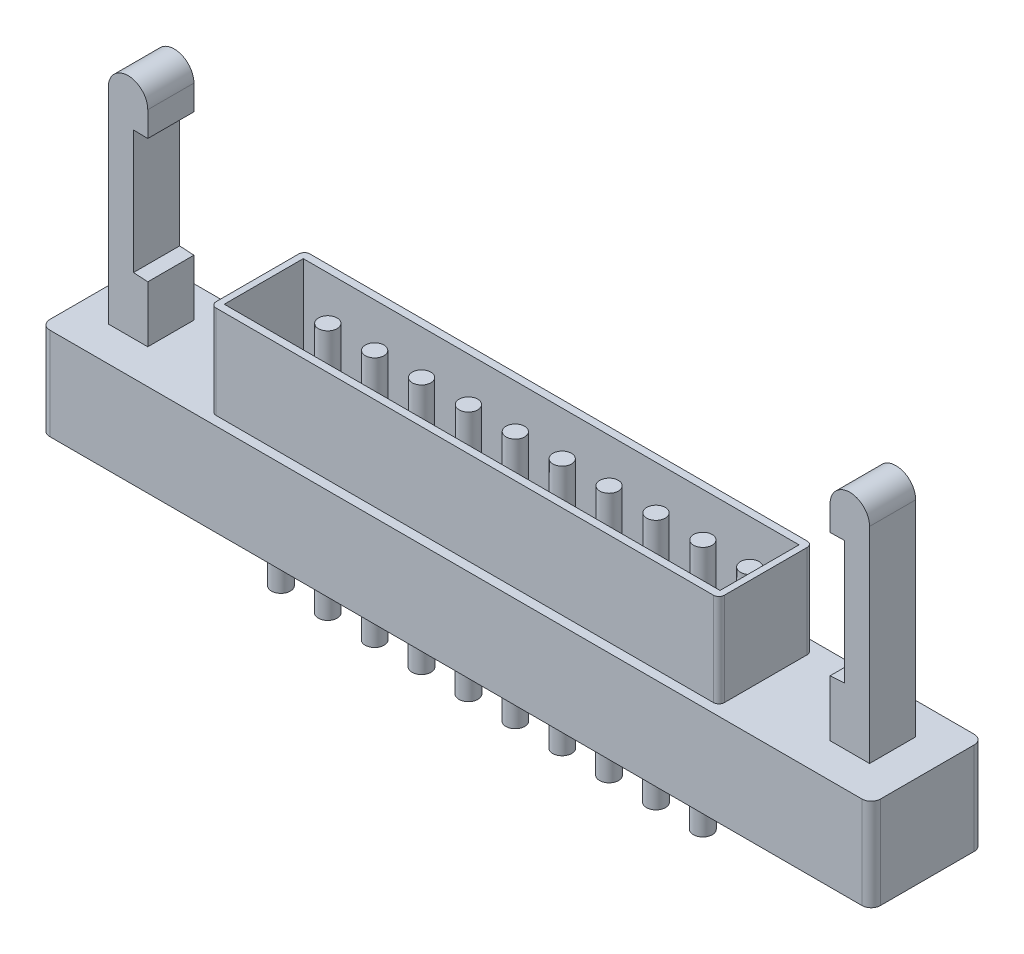
SolidWorks part; units mm, degrees
ref_plane "Спереди" through (0, 0, 0) normal (0, 0, 1) x (1, 0, 0)
ref_plane "Сверху" through (0, 0, 0) normal (0, 1, 0) x (1, 0, 0)
ref_plane "Справа" through (0, 0, 0) normal (1, 0, 0) x (0, 0, -1)
sketch "Эскиз2" plane through (0, 0, 0) normal (0, 0, 1) x (1, 0, 0)
  line L0 (13.77, 7.4474) -> (13.77, -4.0545) construction
  line L1 (0, 0) -> (27.54, 0)
  line L2 (0, 0) -> (0, 2.54)
  line L3 (0, 7.62) -> (27.54, 7.62)
  line L4 (27.54, 0) -> (27.54, 2.54)
  line L5 (1.73, 5) -> (25.81, 5)
  line L6 (1.73, 5) -> (1.73, 6)
  line L7 (1.73, 6) -> (25.81, 6)
  line L8 (25.81, 5) -> (25.81, 6)
  line L9 (27.54, 3.34) -> (27.54, 7.62)
  line L10 (0, 3.34) -> (0.3, 3.34)
  line L12 (0, 2.54) -> (0.3, 2.54)
  line L13 (0.3, 3.34) -> (0.3, 2.54)
  line L14 (27.54, 3.34) -> (27.24, 3.34)
  line L15 (0, 3.34) -> (0, 7.62)
  line L16 (27.54, 2.54) -> (27.24, 2.54)
  line L17 (27.24, 3.34) -> (27.24, 2.54)
  dimension "D1" = 27.54
  dimension "D2" = 7.62
  dimension "D3" = 1
  dimension "D4" = 5
  dimension "D6" = 0.3
  dimension "D7" = 0.8
  dimension "D8" = 0.8
  dimension "D9" = 0.3
  dimension "D10" = 2.54
  dimension "D11" = 2.54
extrude "Вытянуть1" add sketch "Эскиз2" along normal blind 5.08
sketch "Эскиз3" plane through (0, 0, 0) normal (0, -1, 0) x (1, 0, 0)
  line L0 (0, 0) -> (27.54, 0) construction
  line L1 (0, 5.08) -> (0, 0) construction
  circle A0 centre (2.54, 3.81) radius 0.5141
  circle A1 centre (2.54, 1.27) radius 0.5024
  dimension "D1" = 2.54
  dimension "D2" = 1.27
  dimension "D3" = 2.54
  dimension "D4" = 2.54
extrude "Вытянуть2" add sketch "Эскиз3" along normal blind 2.5
pattern_linear "Линейный массив1" count 10 spacing 2.54 along (1, 0, 0) of "Вытянуть2"
sketch "Эскиз4" plane through (0, 7.62, 0) normal (0, 1, 0) x (-1, 0, 0)
  line L1 (-29.08, -1.7915) -> (1.138, -1.7915)
  line L2 (-29.08, -1.7915) -> (-29.08, 6.6797)
  line L3 (-29.08, 6.6797) -> (1.138, 6.6797)
  line L4 (1.138, -1.7915) -> (1.138, 6.6797)
  line L5 (-27.54, 5.08) -> (-27.54, 0) construction
  circle A0 centre (-2.54, 1.27) radius 0.5024 construction
  circle A1 centre (-25.4, 1.27) radius 0.5024 construction
  dimension "D2" = 3.68
  dimension "D3" = 1.54
  dimension "D1" = 3.678
extrude "Вырез-Вытянуть1" cut sketch "Эскиз4" against normal up to surface (5.08 mm away) up to face at (27.39, 2.54, 2.54)
sketch "Эскиз5" plane through (0, 2.54, 0) normal (0, 1, 0) x (-1, 0, 0)
  circle A0 centre (-25.4, 3.81) radius 0.5141 construction
  circle A1 centre (-22.86, 3.81) radius 0.5141 construction
  circle A2 centre (-20.32, 3.81) radius 0.5141 construction
  circle A3 centre (-17.78, 3.81) radius 0.5141 construction
  circle A4 centre (-15.24, 3.81) radius 0.5141 construction
  circle A5 centre (-12.7, 3.81) radius 0.5141 construction
  circle A6 centre (-10.16, 3.81) radius 0.5141 construction
  circle A7 centre (-7.62, 3.81) radius 0.5141 construction
  circle A8 centre (-5.08, 3.81) radius 0.5141 construction
  circle A9 centre (-2.54, 3.81) radius 0.5141 construction
  circle A10 centre (-2.54, 1.27) radius 0.5024 construction
  circle A11 centre (-5.08, 1.27) radius 0.5024 construction
  circle A12 centre (-7.62, 1.27) radius 0.5024 construction
  circle A13 centre (-10.16, 1.27) radius 0.5024 construction
  circle A14 centre (-12.7, 1.27) radius 0.5024 construction
  circle A15 centre (-15.24, 1.27) radius 0.5024 construction
  circle A16 centre (-17.78, 1.27) radius 0.5024 construction
  circle A17 centre (-20.32, 1.27) radius 0.5024 construction
  circle A18 centre (-22.86, 1.27) radius 0.5024 construction
  circle A19 centre (-25.4, 1.27) radius 0.5024 construction
  circle A20 centre (-25.4, 3.81) radius 0.5141
  circle A21 centre (-22.86, 3.81) radius 0.5141
  circle A22 centre (-20.32, 3.81) radius 0.5141
  circle A23 centre (-17.78, 3.81) radius 0.5141
  circle A24 centre (-15.24, 3.81) radius 0.5141
  circle A25 centre (-12.7, 3.81) radius 0.5141
  circle A26 centre (-10.16, 3.81) radius 0.5141
  circle A27 centre (-7.62, 3.81) radius 0.5141
  circle A28 centre (-5.08, 3.81) radius 0.5141
  circle A29 centre (-2.54, 3.81) radius 0.5141
  circle A30 centre (-2.54, 1.27) radius 0.5024
  circle A31 centre (-5.08, 1.27) radius 0.5024
  circle A32 centre (-7.62, 1.27) radius 0.5024
  circle A33 centre (-10.16, 1.27) radius 0.5024
  circle A34 centre (-12.7, 1.27) radius 0.5024
  circle A35 centre (-15.24, 1.27) radius 0.5024
  circle A36 centre (-17.78, 1.27) radius 0.5024
  circle A37 centre (-20.32, 1.27) radius 0.5024
  circle A38 centre (-22.86, 1.27) radius 0.5024
  circle A39 centre (-25.4, 1.27) radius 0.5024
extrude "Вытянуть3" add sketch "Эскиз5" along normal blind 6
sketch "Эскиз6" plane through (0, 0, 0) normal (0, -1, 0) x (1, 0, 0)
  line L0 (0, 5.08) -> (27.54, 5.08) construction
  line L1 (-8.71, 5.58) -> (36.29, 5.58)
  line L2 (-8.71, 5.58) -> (-8.71, -0.5)
  line L3 (-8.71, -0.5) -> (36.29, -0.5)
  line L4 (36.29, 5.58) -> (36.29, -0.5)
  line L5 (0, 0) -> (27.54, 0) construction
  line L12 (0, 0) -> (27.54, 0)
  line L13 (0, 5.08) -> (0, 0)
  line L14 (27.54, 5.08) -> (0, 5.08)
  line L15 (27.54, 0) -> (27.54, 5.08)
  line L16 (0, 0) -> (27.54, 0)
  line L17 (0, 5.08) -> (0, 0)
  line L18 (27.54, 5.08) -> (0, 5.08)
  line L19 (27.54, 0) -> (27.54, 5.08)
  dimension "D3" = 45
  dimension "D1" = 0.5
  dimension "D2" = 0.5
  dimension "D4" = 8.75
  dimension "D5" = 0
extrude "Вытянуть4" add sketch "Эскиз6" against normal blind 2.4
sketch "Эскиз7" plane through (0, 2.54, 0) normal (0, 1, 0) x (-1, 0, 0)
  line L0 (-27.2, 4.68) -> (-27.2, 0.4)
  line L1 (-0.3417, 4.68) -> (-27.2, 4.68)
  line L2 (-0.3417, 4.68) -> (-0.3417, 0.4)
  line L3 (-0.3417, 0.4) -> (-27.2, 0.4)
  line L9 (-27.54, 0) -> (0, 0)
  line L10 (0, 0) -> (0, 5.08)
  line L11 (0, 5.08) -> (-27.54, 5.08)
  line L12 (-27.54, 5.08) -> (-27.54, 0)
  line L13 (-27.54, 0) -> (0, 0)
  line L14 (0, 0) -> (0, 5.08)
  line L15 (0, 5.08) -> (-27.54, 5.08)
  line L16 (-27.54, 5.08) -> (-27.54, 0)
  circle A1 centre (-2.54, 3.81) radius 0.5141 construction
  circle A2 centre (-25.4, 3.81) radius 0.5141 construction
  dimension "D1" = 2.1983
  dimension "D2" = 1.8
  dimension "D3" = 0
extrude "Вытянуть6" add sketch "Эскиз7" along normal blind 7.5
sketch "Эскиз8" plane through (0, 2.4, 0) normal (0, 1, 0) x (-1, 0, 0)
  line L4 (8.71, -0.5) -> (8.71, 5.58)
  line L5 (8.71, 5.58) -> (-36.29, 5.58)
  line L6 (-36.29, 5.58) -> (-36.29, -0.5)
  line L7 (-36.29, -0.5) -> (8.71, -0.5)
  line L8 (8.71, -0.5) -> (8.71, 5.58)
  line L9 (8.71, 5.58) -> (-36.29, 5.58)
  line L10 (-36.29, 5.58) -> (-36.29, -0.5)
  line L11 (-36.29, -0.5) -> (8.71, -0.5)
  dimension "D1" = 0
extrude "Вытянуть7" add sketch "Эскиз8" along normal blind 2.6
ref_plane "Плоскость1" through (0, 0, 2.54) normal (0, 0, 1) x (1, 0, 0)
sketch "Эскиз9" plane through (0, 0, 2.54) normal (0, 0, 1) x (1, 0, 0)
  line L0 (13.79, 19.2852) -> (13.79, -8.5629) construction
  line L1 (-6.8302, 5.0809) -> (-4.6925, 5.0809)
  line L2 (-6.8302, 5.0809) -> (-6.8302, 16.2035)
  line L3 (32.2725, 5.0809) -> (32.2725, 8.1292)
  line L4 (-4.6925, 5.0809) -> (-4.6925, 8.1292)
  line L5 (33.045, 8.1786) -> (32.2725, 8.1292)
  line L6 (33.045, 14.8678) -> (33.045, 8.1786)
  line L7 (32.2725, 14.8533) -> (33.045, 14.8678)
  line L8 (32.2725, 14.8533) -> (32.2725, 16.2035)
  line L9 (-8.71, 5) -> (-8.71, 0) construction
  line L10 (36.29, 5) -> (36.29, 0) construction
  line L11 (-4.6925, 14.8533) -> (-5.465, 14.8678)
  line L12 (-5.465, 14.8678) -> (-5.465, 8.1786)
  line L13 (-5.465, 8.1786) -> (-4.6925, 8.1292)
  line L14 (34.4102, 5.0809) -> (34.4102, 16.2035)
  line L15 (34.4102, 5.0809) -> (32.2725, 5.0809)
  line L18 (-4.6925, 14.8533) -> (-4.6925, 16.2035)
  arc A0 (-6.8302, 16.2035) -> (-4.6925, 16.2035) centre (-5.7614, 16.2035) cw
  arc A1 (34.4102, 16.2035) -> (32.2725, 16.2035) centre (33.3414, 16.2035) ccw
  dimension "D1" = 1.3652
extrude "Вытянуть8" add sketch "Эскиз9" along normal blind 1.25 and the other way blind 1.25
fillet "Скругление1" radius 0.3 4 edges at (0, 7.52, 0) (0, 7.52, 5.08) (27.54, 7.52, 0) (27.54, 7.52, 5.08)
fillet "Скругление2" radius 0.5 4 edges at (36.29, 2.5, -0.5) (36.29, 2.5, 5.58) (-8.71, 2.5, 5.58) (-8.71, 2.5, -0.5)
